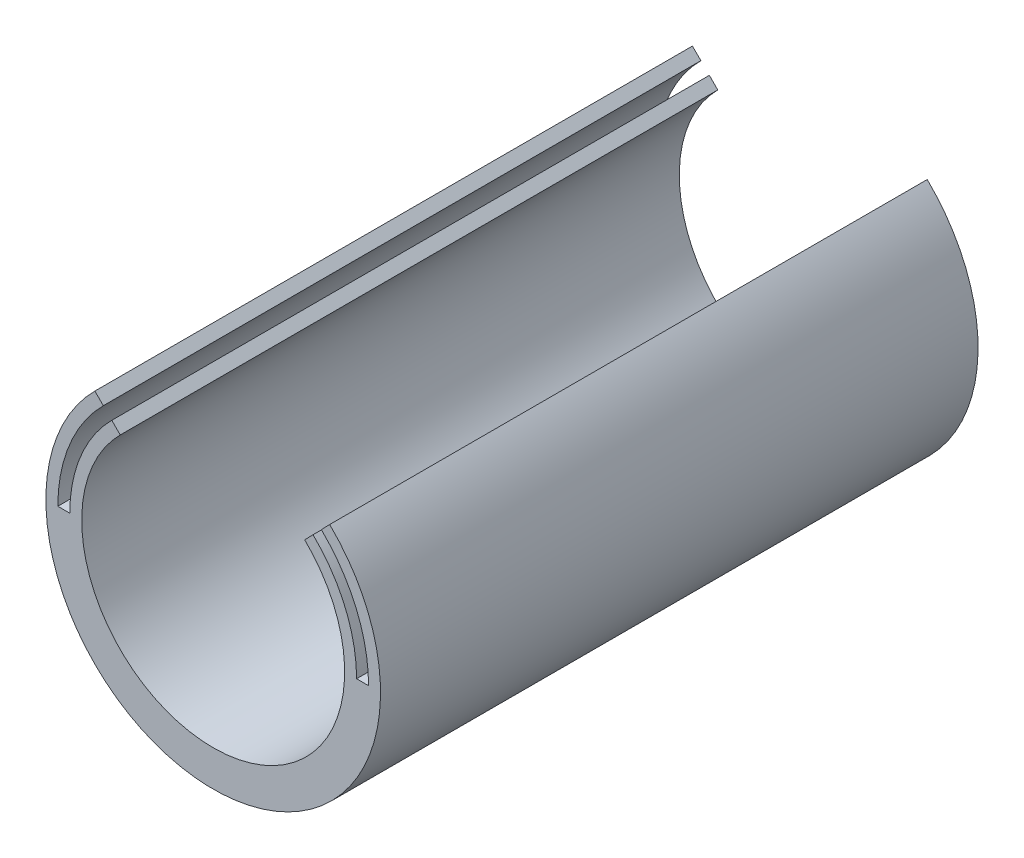
SolidWorks part; units mm, degrees
ref_plane "Plan de face" through (0, 0, 0) normal (0, 0, 1) x (1, 0, 0)
ref_plane "Plan de dessus" through (0, 0, 0) normal (0, 1, 0) x (1, 0, 0)
ref_plane "Plan de droite" through (0, 0, 0) normal (1, 0, 0) x (0, 0, -1)
sketch "Esquisse3" plane through (0, 0, 0) normal (0, 0, 1) x (1, 0, 0)
  arc A0 (21.9974, 0.3384) -> (-22, 0) centre (0, 0) cw
  arc A1 (21.9974, 0.3384) -> (15.3152, 15.7938) centre (0, 0) ccw
  arc A2 (-22, 0) -> (-15.5563, 15.5563) centre (0, 0) cw
extrude "Extru.-Mince2" add sketch "Esquisse3" along normal blind 100 thin thin type one direction wall 6
sketch "Esquisse5" plane through (0, 0, 100) normal (0, 0, 1) x (1, 0, 0)
  arc A0 (23, 0) -> (-23, 0) centre (0, 0) ccw
extrude "Extru.-Mince4" [suppressed] add sketch "Esquisse5" against normal blind 100 thin
sketch "Esquisse7" plane through (0, 0, 100) normal (0, 0, 1) x (1, 0, 0)
  line L0 (-26, 0) -> (-24, 0)
  line L1 (24, 0) -> (26, 0)
  arc A0 (24, 0) -> (-24, 0) centre (0, 0) ccw
  arc A1 (26, 0) -> (-26, 0) centre (0, 0) ccw
extrude "Enlèv. mat.-Extru.2" cut sketch "Esquisse7" against normal blind 100
